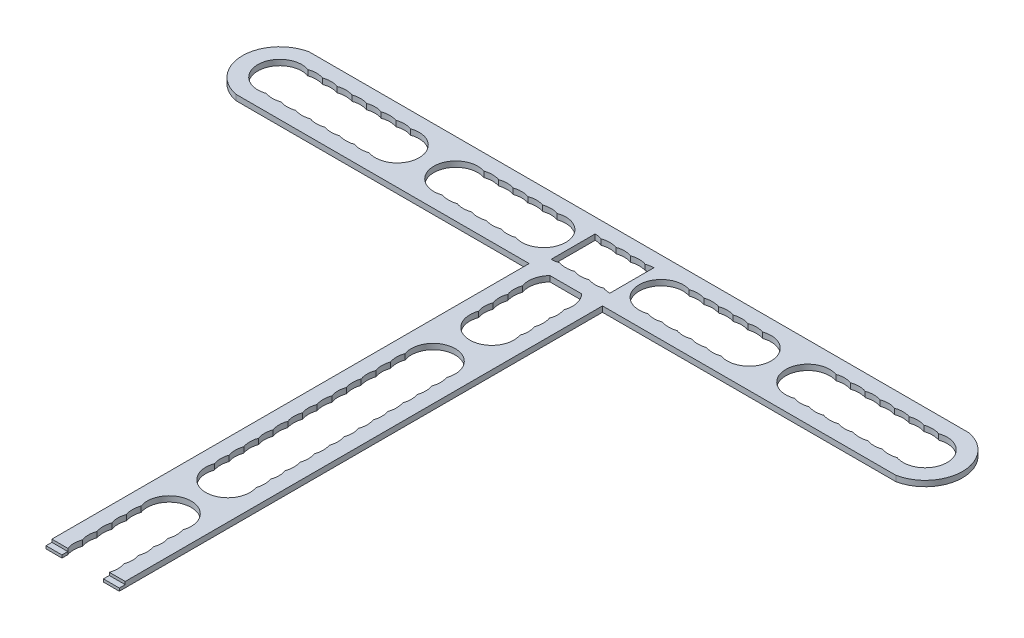
SolidWorks part; units mm, degrees
ref_plane "Front Plane" through (0, 0, 0) normal (0, 0, 1) x (1, 0, 0)
ref_plane "Top Plane" through (0, 0, 0) normal (0, 1, 0) x (1, 0, 0)
ref_plane "Right Plane" through (0, 0, 0) normal (1, 0, 0) x (0, 0, -1)
sketch "Sketch3" plane through (0, 0, 0) normal (0, 1, 0) x (1, 0, 0)
  line L0 (-112.5, 0) -> (112.5, 0) construction
  line L1 (-112.5, -12.5) -> (112.5, -12.5)
  line L2 (-112.5, -12.5) -> (-112.5, 12.5) construction
  line L3 (-112.5, 12.5) -> (112.5, 12.5)
  line L4 (112.5, -12.5) -> (112.5, 12.5) construction
  line L5 (-112.5, -12.5) -> (112.5, 12.5) construction
  line L6 (-112.5, 12.5) -> (112.5, -12.5) construction
  line L7 (60, 12.5) -> (60, -12.5) construction
  line L8 (10, 7.5) -> (10, -7.5)
  line L9 (0, 12.5) -> (0, -12.5) construction
  line L10 (0, 12.5) -> (0, -12.5)
  arc A0 (-2.5, 7.0711) -> (2.5, 7.0711) centre (0, 0) cw
  arc A1 (2.5, 7.0711) -> (7.5, 7.0711) centre (5, 0) cw
  arc A2 (7.5, 7.0711) -> (12.5, 7.0711) centre (10, 0) cw
  arc A3 (12.5, 7.0711) -> (17.5, 7.0711) centre (15, 0) cw
  arc A4 (17.5, 7.0711) -> (22.5, 7.0711) centre (20, 0) cw
  arc A5 (22.5, 7.0711) -> (27.5, 7.0711) centre (25, 0) cw
  arc A6 (27.5, 7.0711) -> (32.5, 7.0711) centre (30, 0) cw
  arc A7 (32.5, 7.0711) -> (37.5, 7.0711) centre (35, 0) cw
  arc A8 (37.5, 7.0711) -> (42.5, 7.0711) centre (40, 0) cw
  arc A9 (42.5, 7.0711) -> (47.5, 7.0711) centre (45, 0) cw
  arc A10 (47.5, 7.0711) -> (52.5, 7.0711) centre (50, 0) cw
  arc A11 (52.5, 7.0711) -> (57.5, 7.0711) centre (55, 0) cw
  arc A12 (57.5, 7.0711) -> (62.5, 7.0711) centre (60, 0) cw
  arc A13 (62.5, 7.0711) -> (67.5, 7.0711) centre (65, 0) cw
  arc A14 (67.5, 7.0711) -> (72.5, 7.0711) centre (70, 0) cw
  arc A15 (72.5, 7.0711) -> (77.5, 7.0711) centre (75, 0) cw
  arc A16 (77.5, 7.0711) -> (82.5, 7.0711) centre (80, 0) cw
  arc A17 (82.5, 7.0711) -> (87.5, 7.0711) centre (85, 0) cw
  arc A18 (87.5, 7.0711) -> (92.5, 7.0711) centre (90, 0) cw
  arc A19 (92.5, 7.0711) -> (97.5, 7.0711) centre (95, 0) cw
  arc A20 (97.5, 7.0711) -> (102.5, 7.0711) centre (100, 0) cw
  arc A21 (102.5, 7.0711) -> (107.5, 7.0711) centre (105, 0) cw
  arc A22 (107.5, 7.0711) -> (112.5, 7.0711) centre (110, 0) cw
  arc A23 (107.5, -7.0711) -> (112.5, -7.0711) centre (110, 0) ccw
  arc A24 (102.5, -7.0711) -> (107.5, -7.0711) centre (105, 0) ccw
  arc A25 (97.5, -7.0711) -> (102.5, -7.0711) centre (100, 0) ccw
  arc A26 (92.5, -7.0711) -> (97.5, -7.0711) centre (95, 0) ccw
  arc A27 (87.5, -7.0711) -> (92.5, -7.0711) centre (90, 0) ccw
  arc A28 (82.5, -7.0711) -> (87.5, -7.0711) centre (85, 0) ccw
  arc A29 (77.5, -7.0711) -> (82.5, -7.0711) centre (80, 0) ccw
  arc A30 (72.5, -7.0711) -> (77.5, -7.0711) centre (75, 0) ccw
  arc A31 (67.5, -7.0711) -> (72.5, -7.0711) centre (70, 0) ccw
  arc A32 (62.5, -7.0711) -> (67.5, -7.0711) centre (65, 0) ccw
  arc A33 (57.5, -7.0711) -> (62.5, -7.0711) centre (60, 0) ccw
  arc A34 (52.5, -7.0711) -> (57.5, -7.0711) centre (55, 0) ccw
  arc A35 (47.5, -7.0711) -> (52.5, -7.0711) centre (50, 0) ccw
  arc A36 (42.5, -7.0711) -> (47.5, -7.0711) centre (45, 0) ccw
  arc A37 (37.5, -7.0711) -> (42.5, -7.0711) centre (40, 0) ccw
  arc A38 (32.5, -7.0711) -> (37.5, -7.0711) centre (35, 0) ccw
  arc A39 (27.5, -7.0711) -> (32.5, -7.0711) centre (30, 0) ccw
  arc A40 (22.5, -7.0711) -> (27.5, -7.0711) centre (25, 0) ccw
  arc A41 (17.5, -7.0711) -> (22.5, -7.0711) centre (20, 0) ccw
  arc A42 (12.5, -7.0711) -> (17.5, -7.0711) centre (15, 0) ccw
  arc A43 (7.5, -7.0711) -> (12.5, -7.0711) centre (10, 0) ccw
  arc A44 (2.5, -7.0711) -> (7.5, -7.0711) centre (5, 0) ccw
  arc A45 (-2.5, -7.0711) -> (2.5, -7.0711) centre (0, 0) ccw
  arc A46 (112.5, 7.0711) -> (112.5, -7.0711) centre (110, 0) cw
  arc A47 (112.5, 12.5) -> (112.5, -12.5) centre (110, 0) cw
  arc A48 (52.5, 7.0711) -> (52.5, -7.0711) centre (50, 0) cw
  arc A49 (67.5, 7.0711) -> (67.5, -7.0711) centre (70, 0) ccw
  arc A50 (17.5, 7.0711) -> (17.5412, -7.0855) centre (20, 0) ccw
  point P0 (0, 0)
  dimension "D4" = 7.5
  dimension "D1" = 225
  dimension "D2" = 25
  dimension "D3" = 5
  dimension "D6" = 60
  dimension "D5" = 23
extrude "Boss-Extrude1" add sketch "Sketch3" along normal blind 1.9 contours A47 L3 L10 A0 A1 A2 A3 A4 A5 A6 A7 A8 A9 A10 A11 A12 A13 A14 A15 A16 A17 A18 A19 A20 A21 A22 A46 A23 A24 A25 A26 A27 A28 A29 A30 A31 A32 A33 A34 A35 A36 A37 A38 A39 A40 A41 A42 A43 | A50 A3 A2 L8 A43 A42 | A49 A13 A12 A11 A48 A34 A33 A32
mirror "Mirror1" about plane through (0, 0, 0) normal (1, 0, 0) of "Boss-Extrude1"
sketch "Sketch4" plane through (0, 0, 0) normal (0, 1, 0) x (1, 0, 0)
  line L0 (-112.5, -12.5) -> (112.5, -12.5) construction
  line L1 (-12.5, -382.9289) -> (12.5, -382.9289)
  line L2 (-12.5, -382.9289) -> (-12.5, -12.5)
  line L3 (-12.5, -12.5) -> (12.5, -12.5)
  line L4 (12.5, -382.9289) -> (12.5, -12.5)
  line L5 (-12.5, -382.9289) -> (12.5, -12.5) construction
  line L6 (-12.5, -12.5) -> (12.5, -382.9289) construction
  line L7 (0, 0) -> (0, -382.9289) construction
  line L8 (-12.5, -175.2145) -> (12.5, -175.2145)
  line L9 (-12.5, -46.875) -> (12.5, -46.875) construction
  line L10 (-12.5, -140.625) -> (12.5, -140.625) construction
  arc A0 (7.0711, -195.2145) -> (7.0711, -200.2145) centre (0, -197.7145) cw
  arc A1 (7.0711, -190.2145) -> (7.0711, -195.2145) centre (0, -192.7145) cw
  arc A2 (7.0711, -185.2145) -> (7.0711, -190.2145) centre (0, -187.7145) cw
  arc A3 (7.0711, -180.2145) -> (7.0711, -185.2145) centre (0, -182.7145) cw
  arc A4 (7.0711, -175.2145) -> (7.0711, -180.2145) centre (0, -177.7145) cw
  arc A5 (7.0711, -170.2145) -> (7.0711, -175.2145) centre (0, -172.7145) cw
  arc A6 (7.0711, -165.2145) -> (7.0711, -170.2145) centre (0, -167.7145) cw
  arc A7 (7.0711, -160.2145) -> (7.0711, -165.2145) centre (0, -162.7145) cw
  arc A8 (7.0711, -155.2145) -> (7.0711, -160.2145) centre (0, -157.7145) cw
  arc A9 (7.0711, -150.2145) -> (7.0711, -155.2145) centre (0, -152.7145) cw
  arc A10 (7.0711, -145.2145) -> (7.0711, -150.2145) centre (0, -147.7145) cw
  arc A11 (7.0711, -140.2145) -> (7.0711, -145.2145) centre (0, -142.7145) cw
  arc A12 (7.0711, -135.2145) -> (7.0711, -140.2145) centre (0, -137.7145) cw
  arc A13 (7.0711, -130.2145) -> (7.0711, -135.2145) centre (0, -132.7145) cw
  arc A14 (7.0711, -125.2145) -> (7.0711, -130.2145) centre (0, -127.7145) cw
  arc A15 (7.0711, -120.2145) -> (7.0711, -125.2145) centre (0, -122.7145) cw
  arc A16 (7.0711, -115.2145) -> (7.0711, -120.2145) centre (0, -117.7145) cw
  arc A17 (7.0711, -110.2145) -> (7.0711, -115.2145) centre (0, -112.7145) cw
  arc A18 (7.0711, -105.2145) -> (7.0711, -110.2145) centre (0, -107.7145) cw
  arc A19 (7.0711, -100.2145) -> (7.0711, -105.2145) centre (0, -102.7145) cw
  arc A20 (7.0711, -95.2145) -> (7.0711, -100.2145) centre (0, -97.7145) cw
  arc A21 (7.0711, -90.2145) -> (7.0711, -95.2145) centre (0, -92.7145) cw
  arc A22 (7.0711, -85.2145) -> (7.0711, -90.2145) centre (0, -87.7145) cw
  arc A23 (7.0711, -80.2145) -> (7.0711, -85.2145) centre (0, -82.7145) cw
  arc A24 (7.0711, -75.2145) -> (7.0711, -80.2145) centre (0, -77.7145) cw
  arc A25 (7.0711, -70.2145) -> (7.0711, -75.2145) centre (0, -72.7145) cw
  arc A26 (7.0711, -65.2145) -> (7.0711, -70.2145) centre (0, -67.7145) cw
  arc A27 (7.0711, -60.2145) -> (7.0711, -65.2145) centre (0, -62.7145) cw
  arc A28 (7.0711, -55.2145) -> (7.0711, -60.2145) centre (0, -57.7145) cw
  arc A29 (7.0711, -50.2145) -> (7.0711, -55.2145) centre (0, -52.7145) cw
  arc A30 (7.0711, -45.2145) -> (7.0711, -50.2145) centre (0, -47.7145) cw
  arc A31 (7.0711, -40.2145) -> (7.0711, -45.2145) centre (0, -42.7145) cw
  arc A32 (7.0711, -35.2145) -> (7.0711, -40.2145) centre (0, -37.7145) cw
  arc A33 (7.0711, -30.2145) -> (7.0711, -35.2145) centre (0, -32.7145) cw
  arc A34 (7.0711, -25.2145) -> (7.0711, -30.2145) centre (0, -27.7145) cw
  arc A35 (7.0711, -20.2145) -> (7.0711, -25.2145) centre (0, -22.7145) cw
  arc A36 (7.0711, -15.2145) -> (7.0711, -20.2145) centre (0, -17.7145) cw
  arc A37 (-7.0711, -195.2145) -> (-7.0711, -200.2145) centre (0, -197.7145) ccw
  arc A38 (-7.0711, -190.2145) -> (-7.0711, -195.2145) centre (0, -192.7145) ccw
  arc A39 (-7.0711, -185.2145) -> (-7.0711, -190.2145) centre (0, -187.7145) ccw
  arc A40 (-7.0711, -180.2145) -> (-7.0711, -185.2145) centre (0, -182.7145) ccw
  arc A41 (-7.0711, -175.2145) -> (-7.0711, -180.2145) centre (0, -177.7145) ccw
  arc A42 (-7.0711, -170.2145) -> (-7.0711, -175.2145) centre (0, -172.7145) ccw
  arc A43 (-7.0711, -165.2145) -> (-7.0711, -170.2145) centre (0, -167.7145) ccw
  arc A44 (-7.0711, -160.2145) -> (-7.0711, -165.2145) centre (0, -162.7145) ccw
  arc A45 (-7.0711, -155.2145) -> (-7.0711, -160.2145) centre (0, -157.7145) ccw
  arc A46 (-7.0711, -150.2145) -> (-7.0711, -155.2145) centre (0, -152.7145) ccw
  arc A47 (-7.0711, -145.2145) -> (-7.0711, -150.2145) centre (0, -147.7145) ccw
  arc A48 (-7.0711, -140.2145) -> (-7.0711, -145.2145) centre (0, -142.7145) ccw
  arc A49 (-7.0711, -135.2145) -> (-7.0711, -140.2145) centre (0, -137.7145) ccw
  arc A50 (-7.0711, -130.2145) -> (-7.0711, -135.2145) centre (0, -132.7145) ccw
  arc A51 (-7.0711, -125.2145) -> (-7.0711, -130.2145) centre (0, -127.7145) ccw
  arc A52 (-7.0711, -120.2145) -> (-7.0711, -125.2145) centre (0, -122.7145) ccw
  arc A53 (-7.0711, -115.2145) -> (-7.0711, -120.2145) centre (0, -117.7145) ccw
  arc A54 (-7.0711, -110.2145) -> (-7.0711, -115.2145) centre (0, -112.7145) ccw
  arc A55 (-7.0711, -105.2145) -> (-7.0711, -110.2145) centre (0, -107.7145) ccw
  arc A56 (-7.0711, -100.2145) -> (-7.0711, -105.2145) centre (0, -102.7145) ccw
  arc A57 (-7.0711, -95.2145) -> (-7.0711, -100.2145) centre (0, -97.7145) ccw
  arc A58 (-7.0711, -90.2145) -> (-7.0711, -95.2145) centre (0, -92.7145) ccw
  arc A59 (-7.0711, -85.2145) -> (-7.0711, -90.2145) centre (0, -87.7145) ccw
  arc A60 (-7.0711, -80.2145) -> (-7.0711, -85.2145) centre (0, -82.7145) ccw
  arc A61 (-7.0711, -75.2145) -> (-7.0711, -80.2145) centre (0, -77.7145) ccw
  arc A62 (-7.0711, -70.2145) -> (-7.0711, -75.2145) centre (0, -72.7145) ccw
  arc A63 (-7.0711, -65.2145) -> (-7.0711, -70.2145) centre (0, -67.7145) ccw
  arc A64 (-7.0711, -60.2145) -> (-7.0711, -65.2145) centre (0, -62.7145) ccw
  arc A65 (-7.0711, -55.2145) -> (-7.0711, -60.2145) centre (0, -57.7145) ccw
  arc A66 (-7.0711, -50.2145) -> (-7.0711, -55.2145) centre (0, -52.7145) ccw
  arc A67 (-7.0711, -45.2145) -> (-7.0711, -50.2145) centre (0, -47.7145) ccw
  arc A68 (-7.0711, -40.2145) -> (-7.0711, -45.2145) centre (0, -42.7145) ccw
  arc A69 (-7.0711, -35.2145) -> (-7.0711, -40.2145) centre (0, -37.7145) ccw
  arc A70 (-7.0711, -30.2145) -> (-7.0711, -35.2145) centre (0, -32.7145) ccw
  arc A71 (-7.0711, -25.2145) -> (-7.0711, -30.2145) centre (0, -27.7145) ccw
  arc A72 (-7.0711, -20.2145) -> (-7.0711, -25.2145) centre (0, -22.7145) ccw
  arc A73 (-7.0711, -15.2145) -> (-7.0711, -20.2145) centre (0, -17.7145) ccw
  arc A74 (7.0711, -15.2145) -> (-7.0711, -15.2145) centre (0, -17.7145) ccw
  arc A75 (-7.0711, -40.2145) -> (7.0711, -40.2145) centre (0, -37.7145) ccw
  arc A76 (7.0711, -55.2145) -> (-7.0711, -55.2145) centre (0, -57.7145) ccw
  arc A77 (-7.0711, -130.2145) -> (7.0711, -130.2145) centre (0, -127.7145) ccw
  arc A78 (7.0711, -145.2145) -> (-7.0711, -145.2145) centre (0, -147.7145) ccw
  point P0 (0, -197.7145)
  point P134 (0, 0)
  dimension "D4" = 7.5
  dimension "D3" = 5
  dimension "D1" = 25
  dimension "D2" = 390
  dimension "D6" = 46.875
  dimension "D7" = 93.75
  dimension "D5" = 37
extrude "Boss-Extrude2" add sketch "Sketch4" along normal blind 1.9
sketch "Sketch5" plane through (0, 0, 0) normal (0, 1, 0) x (1, 0, 0)
  line L1 (-12.5, -175.2145) -> (-7.0711, -175.2145)
  line L2 (-12.5, -175.2145) -> (-12.5, -177.2145)
  line L3 (-12.5, -177.2145) -> (-7.0711, -177.2145)
  line L4 (-7.0711, -175.2145) -> (-7.0711, -177.2145)
  line L5 (7.0711, -175.2145) -> (12.5, -175.2145)
  line L6 (7.0711, -175.2145) -> (7.0711, -177.2145)
  line L7 (7.0711, -177.2145) -> (12.5, -177.2145)
  line L8 (12.5, -175.2145) -> (12.5, -177.2145)
  point P5 (0, 0)
  dimension "D1" = 2
extrude "Boss-Extrude3" add sketch "Sketch5" along normal blind 0.95
equation "\"diameter_electrode_outer\"= 15mm"
equation "\"width_wing\"= 5mm"
equation "\"rad_curve\"= \"diameter_electrode_outer\" / 2"
equation "\"length_wing\"= 10mm"
equation "\"range_electrode_move_horizontal\"= ( \"length_wing\" / 2 ) * 66"
equation "\"length_slit_horizontal\"= \"diameter_electrode_outer\" + \"range_electrode_move_horizontal\""
equation "\"width_frame\"= \"diameter_electrode_outer\" + \"width_wing\" * 2"
equation "\"height_frame\"= 1.9mm"
equation "\"diameter_fluid_tank_outer\"= 60mm"
equation "\"width_frame_support\"= 10mm"
equation "\"D1@Fillet2\"=\"rad_curve\""
equation "\"range_electrode_move_vertical\"= ( \"length_wing\" / 2 ) * 75"
equation "\"length_slit_vertical\"= \"diameter_electrode_outer\" + \"range_electrode_move_vertical\""
equation "\"circumference_head\"= 600mm"
equation "\"range_electrode_move_front\"= \"circumference_head\" * 3.5 / 10"
equation "\"length_slit_front\"= \"range_electrode_move_front\" + \"diameter_electrode_outer\""
equation "\"D1@Sketch3\"=\"length_slit_front\""
equation "\"D2@Sketch3\"=\"diameter_electrode_outer\"+2*\"width_wing\""
equation "\"D3@Sketch3\"=\"length_wing\"/2"
equation "\"D4@Sketch3\"=\"rad_curve\""
equation "\"D6@Sketch3\"=\"circumference_head\"/10"
equation "\"D1@Boss-Extrude1\"=\"height_frame\""
equation "\"D1@Sketch4\"=\"diameter_electrode_outer\"+2*\"width_wing\""
equation "\"D2@Sketch4\"=\"length_slit_vertical\""
equation "\"D3@Sketch4\"=\"length_wing\"/2"
equation "\"D4@Sketch4\"=\"rad_curve\""
equation "\"D6@Sketch4\"=\"range_electrode_move_vertical\"*0.5/4"
equation "\"D7@Sketch4\"=\"range_electrode_move_vertical\"/4"
equation "\"D1@Boss-Extrude2\"=\"height_frame\""
equation "\"width_connect\"= 2mm"
equation "\"height_connect\"= \"height_frame\" / 2"
equation "\"D1@Boss-Extrude3\"=\"height_connect\""
equation "\"D1@Sketch5\"=\"width_connect\""
equation "\"length_slit_vertical\"= \"range_electrode_move_vertical\" + \"diameter_electrode_outer\""
